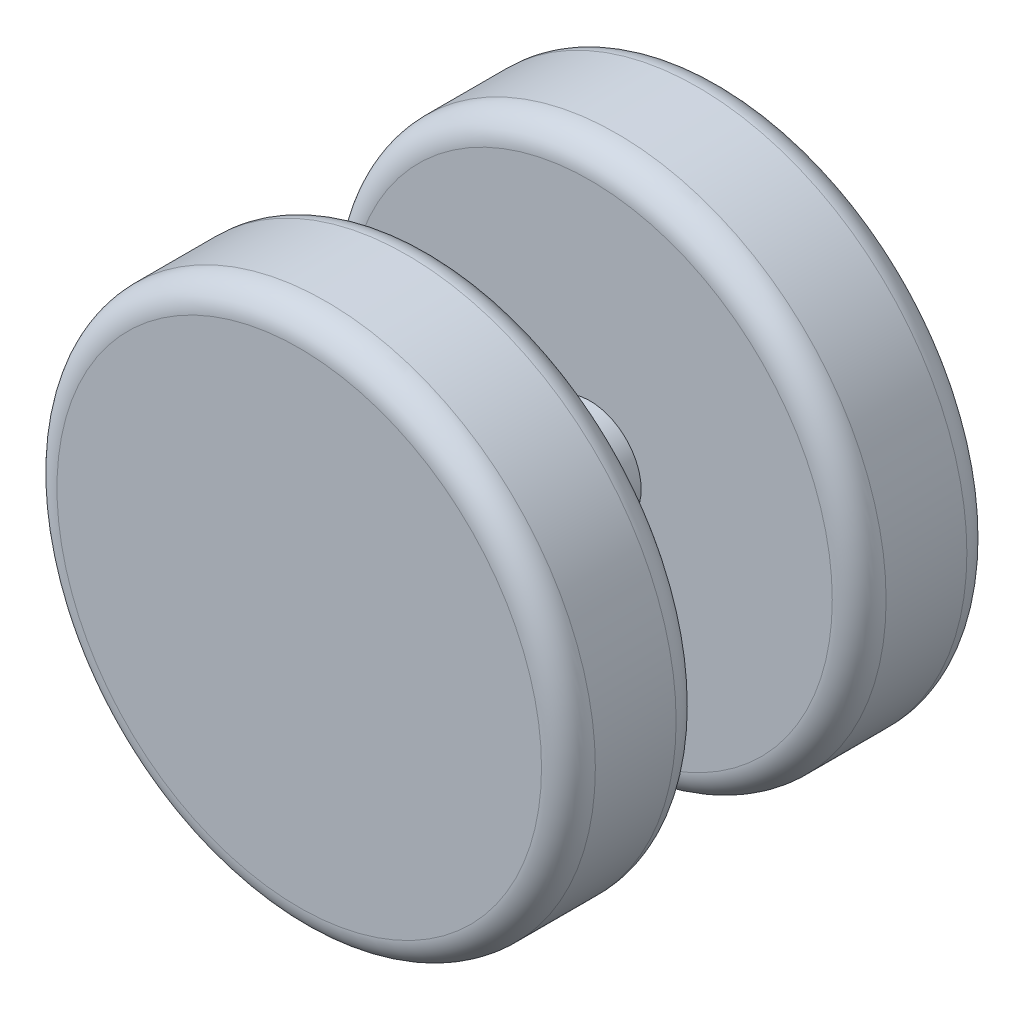
SolidWorks part; units mm, degrees
ref_plane "Front Plane" through (0, 0, 0) normal (0, 0, 1) x (1, 0, 0)
ref_plane "Top Plane" through (0, 0, 0) normal (0, 1, 0) x (1, 0, 0)
ref_plane "Right Plane" through (0, 0, 0) normal (1, 0, 0) x (0, 0, -1)
sketch "Sketch1" plane through (0, 0, 0) normal (0, 0, 1) x (1, 0, 0)
  circle A0 centre (0, 0) radius 5
  dimension "D1" = 10
extrude "Boss-Extrude1" add sketch "Sketch1" along normal blind 2.5
fillet "Fillet1" radius 0.5 1 edges at (5, 0, 0)
fillet "Fillet2" radius 0.5 1 edges at (5, 0, 2.5)
sketch "Sketch2" plane through (0, 0, 2.5) normal (0, 0, 1) x (1, 0, 0)
  circle A0 centre (0, 0) radius 0.95
  dimension "D1" = 1.9
extrude "Boss-Extrude2" add sketch "Sketch2" along normal blind 2.9
sketch "Sketch3" plane through (0, 0, 5.4) normal (0, 0, 1) x (1, 0, 0)
  circle A0 centre (0, 0) radius 5
  dimension "D1" = 10
extrude "Boss-Extrude3" add sketch "Sketch3" along normal blind 2.5
fillet "Fillet3" radius 0.5 2 edges at (5, 0, 5.4) (5, 0, 7.9)
